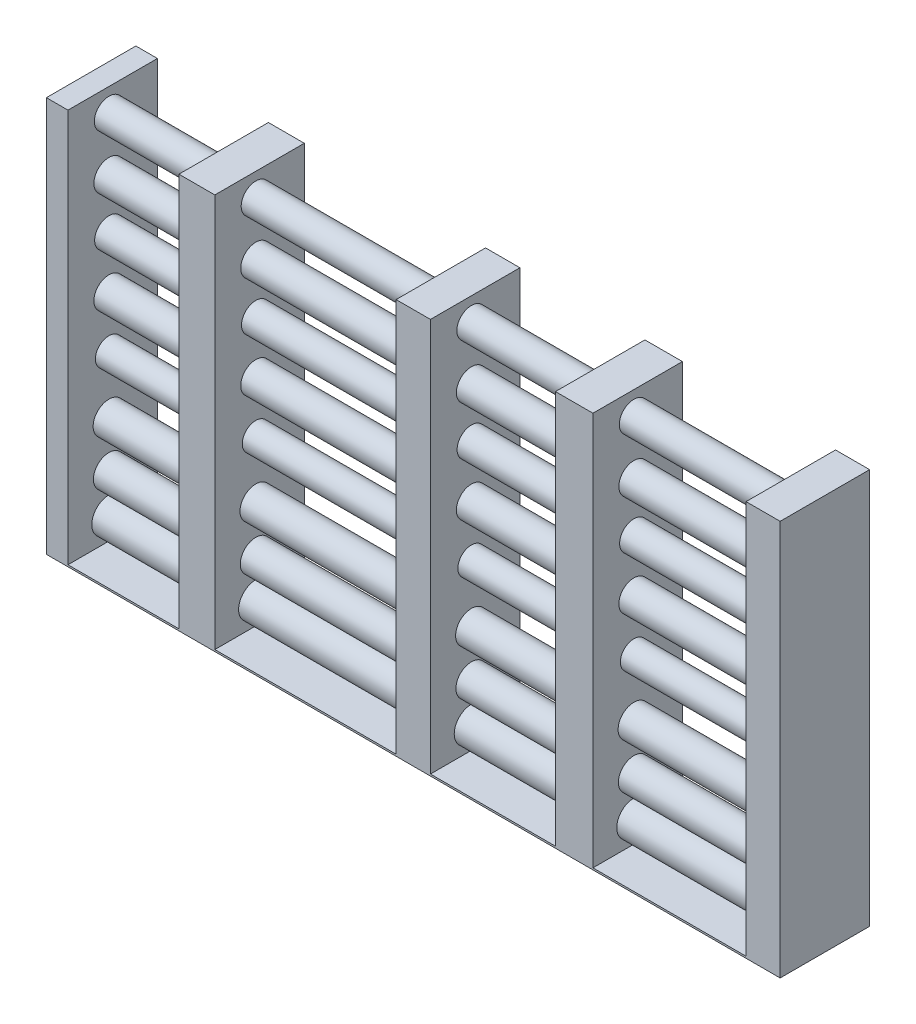
SolidWorks part; units mm, degrees
ref_plane "Front Plane" through (0, 0, 0) normal (0, 0, 1) x (1, 0, 0)
ref_plane "Top Plane" through (0, 0, 0) normal (0, 1, 0) x (1, 0, 0)
ref_plane "Right Plane" through (0, 0, 0) normal (1, 0, 0) x (0, 0, -1)
sketch "Sketch1" plane through (0, 0, 0) normal (0, 0, 1) x (1, 0, 0)
  line L1 (-41, -22) -> (41, -22)
  line L2 (-41, -22) -> (-41, 22)
  line L3 (-41, 22) -> (41, 22)
  line L4 (41, -22) -> (41, 22)
  line L5 (-41, -22) -> (41, 22) construction
  line L6 (-41, 22) -> (41, -22) construction
  line L7 (-41, 22) -> (-38.5873, 22)
  line L8 (-41, 22) -> (-41, -22)
  line L9 (-41, -22) -> (-38.5873, -22)
  line L10 (-38.5873, 22) -> (-38.5873, -22)
  line L11 (41, 22) -> (37.1905, 22)
  line L12 (41, 22) -> (41, -22)
  line L13 (41, -22) -> (37.1905, -22)
  line L14 (37.1905, 22) -> (37.1905, -22)
  line L15 (-1.9206, -22) -> (1.9206, -22)
  line L16 (-1.9206, -22) -> (-1.9206, 22)
  line L17 (-1.9206, 22) -> (1.9206, 22)
  line L18 (1.9206, -22) -> (1.9206, 22)
  line L19 (-1.9206, -22) -> (1.9206, 22) construction
  line L20 (-1.9206, 22) -> (1.9206, -22) construction
  line L21 (-26.1905, 22) -> (-22.1746, 22)
  line L22 (-26.1905, 22) -> (-26.1905, -22)
  line L23 (-26.1905, -22) -> (-22.1746, -22)
  line L24 (-22.1746, 22) -> (-22.1746, -22)
  line L25 (15.8889, 22) -> (20.0794, 22)
  line L26 (15.8889, 22) -> (15.8889, -22)
  line L27 (15.8889, -22) -> (20.0794, -22)
  line L28 (20.0794, 22) -> (20.0794, -22)
  point P0 (0, 0)
  point P10 (0, 0)
  dimension "D1" = 44
  dimension "D2" = 82
extrude "Boss-Extrude1" add sketch "Sketch1" along normal blind 10 contours L10 L3 L2 L1 | L24 L3 L22 L1 | L28 L3 L26 L1 | L3 L14 L1 L4 | L1 L18 L3 L16
sketch "Sketch2" plane through (-38.5873, 0, 0) normal (1, 0, 0) x (0, 0, -1)
  circle A0 centre (-5.4209, 19.4258) radius 1.6339
  circle A1 centre (-5.4209, 13.451) radius 1.6831
  circle A2 centre (-5.4209, 7.8969) radius 1.5989
  circle A3 centre (-5.4209, 2.0904) radius 1.6831
  circle A4 centre (-5.4209, -3.632) radius 1.5147
  circle A5 centre (-5.4209, -10.0276) radius 1.7672
  circle A6 centre (-5.4209, -15.1609) radius 1.7349
  circle A7 centre (-5.4209, -19.4527) radius 1.9208
extrude "Boss-Extrude2" add sketch "Sketch2" along normal blind 79
sketch "Sketch3" plane through (0, -22, 0) normal (0, -1, 0) x (1, 0, 0)
  line L1 (37.417, 0.2832) -> (40.8321, 0.2832)
  line L2 (37.417, 0.2832) -> (37.417, 9.6584)
  line L3 (37.417, 9.6584) -> (40.8321, 9.6584)
  line L4 (40.8321, 0.2832) -> (40.8321, 9.6584)
extrude "Cut-Extrude1" cut sketch "Sketch3" against normal blind 43
sketch "Sketch4" plane through (0, -22, 0) normal (0, -1, 0) x (1, 0, 0)
  line L1 (16.2255, 0.4479) -> (19.5113, 0.4479)
  line L2 (16.2255, 0.4479) -> (16.2255, 9.5692)
  line L3 (16.2255, 9.5692) -> (19.5113, 9.5692)
  line L4 (19.5113, 0.4479) -> (19.5113, 9.5692)
extrude "Cut-Extrude2" cut sketch "Sketch4" against normal blind 43
sketch "Sketch5" plane through (0, -22, 0) normal (0, -1, 0) x (1, 0, 0)
  line L1 (-1.5398, 0.3266) -> (1.5315, 0.3266)
  line L2 (-1.5398, 0.3266) -> (-1.5398, 9.6029)
  line L3 (-1.5398, 9.6029) -> (1.5315, 9.6029)
  line L4 (1.5315, 0.3266) -> (1.5315, 9.6029)
extrude "Cut-Extrude3" cut sketch "Sketch5" against normal blind 43
sketch "Sketch6" plane through (0, -22, 0) normal (0, -1, 0) x (1, 0, 0)
  line L1 (-25.9205, 9.7285) -> (-22.4738, 9.7285)
  line L2 (-25.9205, 9.7285) -> (-25.9205, 0.2415)
  line L3 (-25.9205, 0.2415) -> (-22.4738, 0.2415)
  line L4 (-22.4738, 9.7285) -> (-22.4738, 0.2415)
extrude "Cut-Extrude4" cut sketch "Sketch6" against normal blind 43
sketch "Sketch7" plane through (0, -22, 0) normal (0, -1, 0) x (1, 0, 0)
  line L1 (-40.7687, 9.8031) -> (-38.7788, 9.8031)
  line L2 (-40.7687, 9.8031) -> (-40.7687, 0.2515)
  line L3 (-40.7687, 0.2515) -> (-38.7788, 0.2515)
  line L4 (-38.7788, 9.8031) -> (-38.7788, 0.2515)
extrude "Cut-Extrude5" cut sketch "Sketch7" against normal blind 43
sketch "Sketch8" plane through (0, -22, 0) normal (0, -1, 0) x (1, 0, 0)
  line L1 (-41, 10) -> (41, 10)
  line L2 (-41, 10) -> (-41, 0)
  line L3 (-41, 0) -> (41, 0)
  line L4 (41, 10) -> (41, 0)
extrude "Boss-Extrude3" add sketch "Sketch8" along normal blind 0.2
